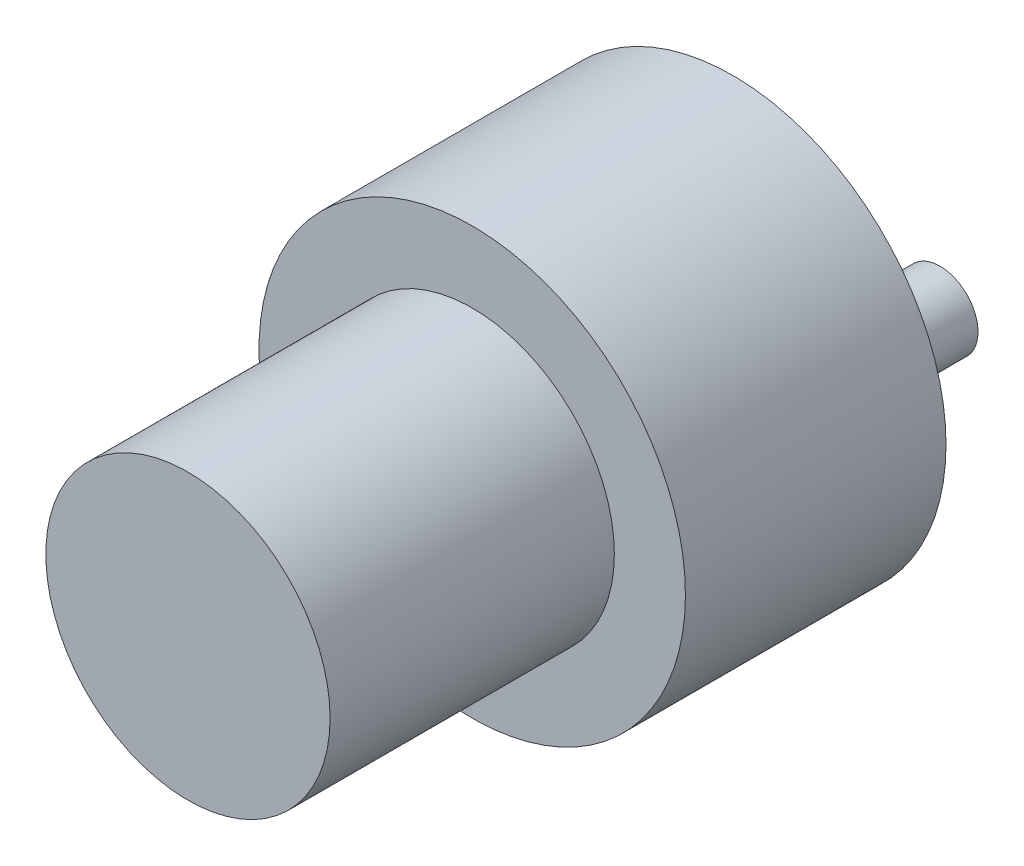
SolidWorks part; units mm, degrees
ref_plane "Front Plane" through (0, 0, 0) normal (0, 0, 1) x (1, 0, 0)
ref_plane "Top Plane" through (0, 0, 0) normal (0, 1, 0) x (1, 0, 0)
ref_plane "Right Plane" through (0, 0, 0) normal (1, 0, 0) x (0, 0, -1)
sketch "Sketch1" plane through (0, 0, 0) normal (0, 0, 1) x (1, 0, 0)
  circle A0 centre (0, 0) radius 22.5
extrude "Boss-Extrude1" add sketch "Sketch1" along normal blind 27.5
sketch "Sketch2" plane through (0, 0, 27.5) normal (0, 0, 1) x (1, 0, 0)
  circle A0 centre (0, 0) radius 15
extrude "Boss-Extrude2" add sketch "Sketch2" along normal blind 30 separate body
sketch "Sketch3" plane through (0, 0, 0) normal (0, 0, -1) x (-1, 0, 0)
  circle A0 centre (-9.8758, 0) radius 4
extrude "Boss-Extrude3" add sketch "Sketch3" along normal blind 12 contours A0
